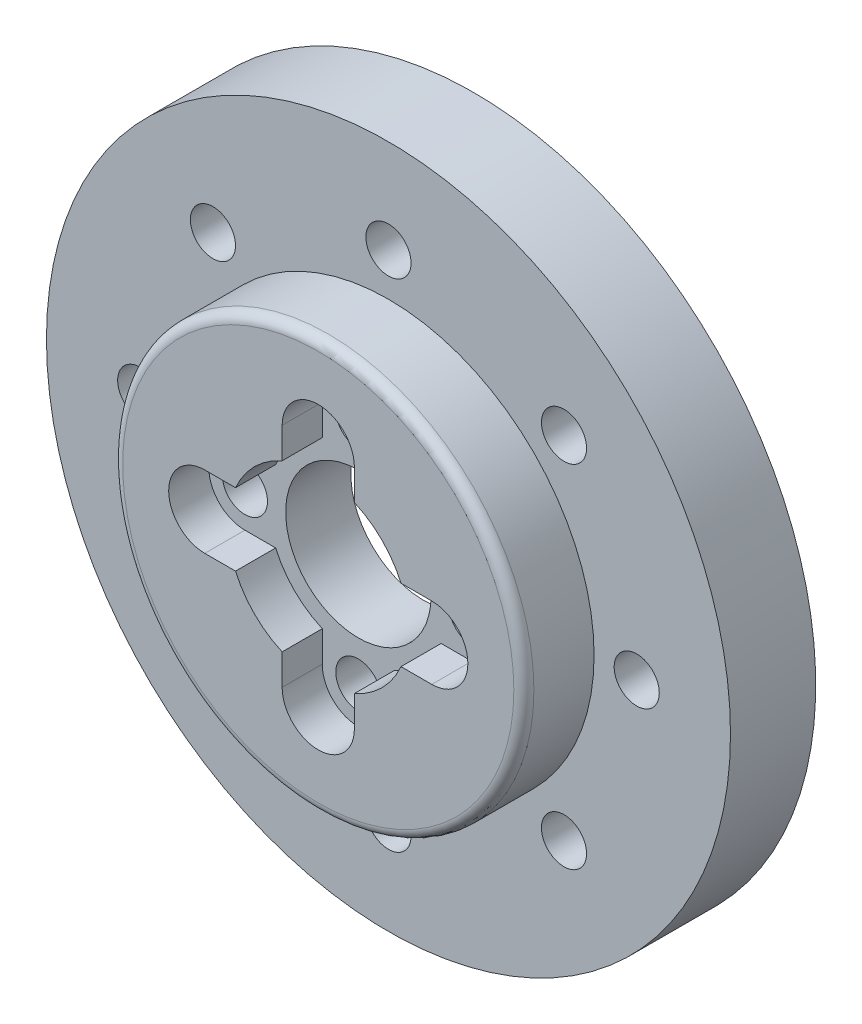
SolidWorks part; units mm, degrees
ref_plane "Front Plane" through (0, 0, 0) normal (0, 0, 1) x (1, 0, 0)
ref_plane "Top Plane" through (0, 0, 0) normal (0, 1, 0) x (1, 0, 0)
ref_plane "Right Plane" through (0, 0, 0) normal (1, 0, 0) x (0, 0, -1)
sketch "Sketch1" plane through (0, 0, 0) normal (0, 0, 1) x (1, 0, 0)
  circle A0 centre (0, 0) radius 34.1
  dimension "D1" = 68.2
extrude "Boss-Extrude1" add sketch "Sketch1" along normal mid plane 3.5
sketch "Sketch4" plane through (0, 0, 1.75) normal (0, 0, 1) x (1, 0, 0)
  circle A0 centre (0, 0) radius 28.5
  dimension "D1" = 57
extrude "Boss-Extrude2" add sketch "Sketch4" along normal blind 2
sketch "Sketch5" plane through (0, 0, -1.75) normal (0, 0, -1) x (-1, 0, 0)
  circle A0 centre (0, 0) radius 16.25
  circle A1 centre (0, 0) radius 34.1 construction
  circle A2 centre (0, 0) radius 34.1
  dimension "D1" = 32.5
extrude "Boss-Extrude3" add sketch "Sketch5" along normal blind 5
sketch "Sketch3" plane through (0, 0, 1.75) normal (0, 0, 1) x (1, 0, 0)
  circle A8 centre (0, 0) radius 11.3137 construction
  circle A9 centre (0, 11.3137) radius 2.25
  circle A11 centre (11.3137, 0) radius 2.25
  circle A13 centre (0, -11.3137) radius 2.25
  circle A15 centre (-11.3137, 0) radius 2.25
  point P21 (0, 0)
  dimension "D3" = 22.6274
  dimension "D4" = 4.5
  dimension "D5" = 4
extrude "Cut-Extrude2" cut sketch "Sketch3" against normal through all both and the other way through all
sketch "Sketch2" plane through (0, 0, 1.75) normal (0, 0, 1) x (1, 0, 0)
  circle A0 centre (0, 0) radius 7.25
  dimension "D1" = 14.5
extrude "Cut-Extrude1" cut sketch "Sketch2" along normal through all both and the other way through all
sketch "Sketch6" plane through (0, 0, 3.75) normal (0, 0, 1) x (1, 0, 0)
  circle A0 centre (0, 24.75) radius 2.25
  dimension "D1" = 4.5
  dimension "D2" = 24.75
extrude "Cut-Extrude3" cut sketch "Sketch6" against normal through all both and the other way through all
pattern_circular "CirPattern1" count 8 over 360 about axis through (0, 0, 0) along (0, 0, 1) of "Cut-Extrude3"
sketch "Sketch7" plane through (0, 0, 3.75) normal (0, 0, 1) x (1, 0, 0)
  circle A0 centre (0, 0) radius 20.5
  circle A5 centre (0, -11.3137) radius 2.25 construction
  circle A6 centre (11.3137, 0) radius 2.25 construction
  circle A7 centre (0, 11.3137) radius 2.25 construction
  circle A8 centre (-11.3137, 0) radius 2.25 construction
  circle A9 centre (0, 0) radius 7.25 construction
  circle A10 centre (0, -11.3137) radius 2.25
  circle A11 centre (11.3137, 0) radius 2.25
  circle A12 centre (0, 11.3137) radius 2.25
  circle A13 centre (-11.3137, 0) radius 2.25
  circle A14 centre (0, 0) radius 7.25
  dimension "D1" = 41
extrude "Boss-Extrude4" add sketch "Sketch7" along normal blind 5
sketch "Sketch8" plane through (0, 0, 1.75) normal (0, 0, 1) x (1, 0, 0)
  circle A0 centre (0, 0) radius 28.5 construction
  circle A1 centre (0, 0) radius 34.1
  circle A2 centre (0, 0) radius 34.1
  circle A3 centre (0, 0) radius 28.5
  dimension "D1" = 0
extrude "Boss-Extrude5" add sketch "Sketch8" along normal up to surface (2 mm away) up to face at (20.5, 0, 3.75)
sketch "Sketch10" plane through (0, 0, 3.75) normal (0, 0, 1) x (1, 0, 0)
  circle A0 centre (0, 0) radius 20.5 construction
  circle A1 centre (0, 0) radius 34.1
  circle A2 centre (0, 0) radius 34.1
  circle A3 centre (0, 0) radius 20.5
  dimension "D1" = 0
extrude "Cut-Extrude4" cut sketch "Sketch10" against normal blind 2
sketch "Sketch11" plane through (0, 0, 8.75) normal (0, 0, 1) x (1, 0, 0)
  line L0 (-11.3137, 3.6) -> (-8.2486, 3.6)
  line L1 (-3.6, 8.2486) -> (-3.6, 11.3137)
  line L2 (3.6, 11.3137) -> (3.6, 8.2486)
  line L3 (8.2486, 3.6) -> (11.3137, 3.6)
  line L4 (11.3137, -3.6) -> (8.2486, -3.6)
  line L5 (3.6, -8.2486) -> (3.6, -11.3137)
  line L6 (-3.6, -11.3137) -> (-3.6, -8.2486)
  line L7 (-8.2486, -3.6) -> (-11.3137, -3.6)
  circle A0 centre (-11.3137, 0) radius 2.25 construction
  circle A1 centre (0, -11.3137) radius 2.25 construction
  circle A2 centre (11.3137, 0) radius 2.25 construction
  circle A3 centre (0, 11.3137) radius 2.25 construction
  circle A4 centre (-11.3137, 0) radius 2.25 construction
  circle A5 centre (0, -11.3137) radius 2.25 construction
  circle A6 centre (11.3137, 0) radius 2.25 construction
  circle A7 centre (0, 11.3137) radius 2.25 construction
  arc A8 (-3.6, -11.3137) -> (3.6, -11.3137) centre (0, -11.3137) ccw
  arc A9 (11.3137, -3.6) -> (11.3137, 3.6) centre (11.3137, 0) ccw
  arc A10 (3.6, 11.3137) -> (-3.6, 11.3137) centre (0, 11.3137) ccw
  arc A11 (-11.3137, 3.6) -> (-11.3137, -3.6) centre (-11.3137, 0) ccw
  arc A12 (-8.2486, -3.6) -> (-3.6, -8.2486) centre (0, 0) ccw
  arc A13 (-3.6, 8.2486) -> (-8.2486, 3.6) centre (0, 0) ccw
  arc A14 (8.2486, 3.6) -> (3.6, 8.2486) centre (0, 0) ccw
  arc A15 (3.6, -8.2486) -> (8.2486, -3.6) centre (0, 0) ccw
  dimension "D1" = 7.2
  dimension "D2" = 18
extrude "Cut-Extrude5" cut sketch "Sketch11" against normal blind 4
sketch "Sketch12" plane through (0, 0, -6.75) normal (0, 0, -1) x (-1, 0, 0)
  circle A0 centre (0, 24.75) radius 4.6
  circle A1 centre (17.5009, 17.5009) radius 4.6
  circle A2 centre (24.75, 0) radius 4.6
  circle A3 centre (17.5009, -17.5009) radius 4.6
  circle A4 centre (0, -24.75) radius 4.6
  circle A5 centre (-17.5009, -17.5009) radius 4.6
  circle A6 centre (-24.75, 0) radius 4.6
  circle A7 centre (-17.5009, 17.5009) radius 4.6
  point P19 (0, 0)
  dimension "D1" = 9.2
  dimension "D2" = 8
extrude "Cut-Extrude6" cut sketch "Sketch12" against normal blind 3
fillet "Fillet2" radius 1 1 edges at (20.5, 0, 8.75)
